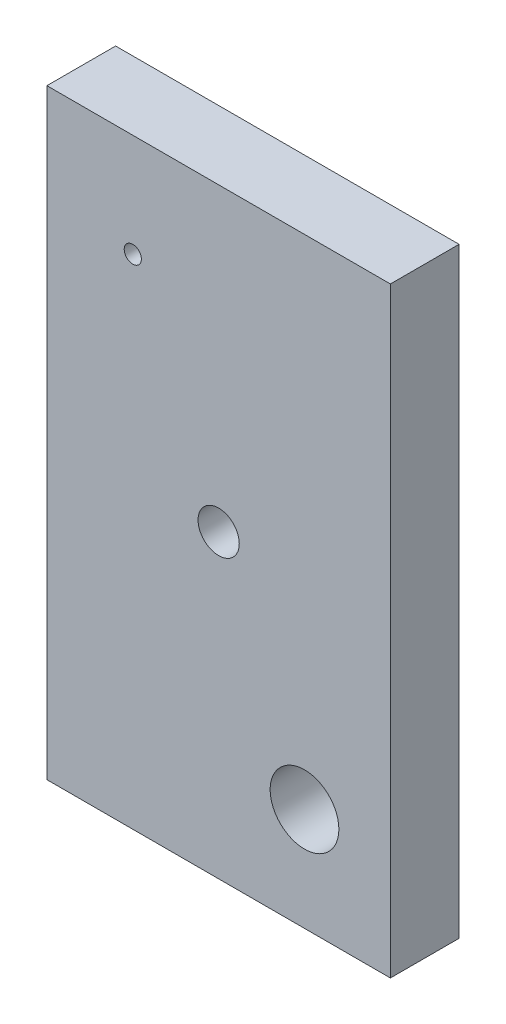
SolidWorks part; units mm, degrees
ref_plane "Front Plane" through (0, 0, 0) normal (0, 0, 1) x (1, 0, 0)
ref_plane "Top Plane" through (0, 0, 0) normal (0, 1, 0) x (1, 0, 0)
ref_plane "Right Plane" through (0, 0, 0) normal (1, 0, 0) x (0, 0, -1)
sketch "Sketch1" plane through (0, 0, 0) normal (0, 0, 1) x (1, 0, 0)
  line L1 (0, 0) -> (100, 0)
  line L2 (0, 0) -> (0, 175)
  line L3 (0, 175) -> (100, 175)
  line L4 (100, 0) -> (100, 175)
  dimension "D1" = 100
  dimension "D2" = 175
extrude "Boss-Extrude1" add sketch "Sketch1" against normal blind 20
hole_wizard "Ø5.0 (5) Diameter Hole1" positions "Sketch2" profile "Sketch3" hole size "Ø5.0" standard "ANSI Metric" end condition through all
sketch "Sketch2" plane through (0, 0, 0) normal (0, 0, 1) x (1, 0, 0)
  line L0 (0, 175) -> (0, 0) construction
  line L1 (100, 175) -> (0, 175) construction
  point P0 (25, 145)
  dimension "D1" = 25
  dimension "D2" = 30
sketch "Sketch3" plane through (25, 145, 0) normal (1, 0, 0) x (0, -1, 0)
  line L0 (0, 0) -> (0, 20)
  line L1 (0, 20) -> (2.5, 20)
  line L2 (2.5, 20) -> (2.5, 0)
  line L5 (2.5, 0) -> (0, 0)
  line L11 (0, -6.35) -> (0, 107.95) construction
  dimension "Thru Hole Dia." = 5
  dimension "Thru Hole Depth" = 20
hole_wizard "Ø12.0 (12) Diameter Hole1" positions "Sketch4" profile "Sketch5" hole size "Ø12.0" standard "ANSI Metric" end condition through all
sketch "Sketch4" plane through (0, 0, 0) normal (0, 0, 1) x (1, 0, 0)
  line L0 (100, 175) -> (0, 175) construction
  line L1 (0, 175) -> (0, 0) construction
  point P0 (50, 87.5)
  dimension "D1" = 87.5
  dimension "D2" = 50
sketch "Sketch5" plane through (50, 87.5, 0) normal (1, 0, 0) x (0, -1, 0)
  line L0 (0, 0) -> (0, 20)
  line L1 (0, 20) -> (6, 20)
  line L2 (6, 20) -> (6, 0)
  line L5 (6, 0) -> (0, 0)
  line L11 (0, -6.35) -> (0, 107.95) construction
  dimension "Thru Hole Dia." = 12
  dimension "Thru Hole Depth" = 20
hole_wizard "Ø20.0 (20) Diameter Hole1" positions "Sketch6" profile "Sketch7" hole size "Ø20.0" standard "ANSI Metric" end condition through all
sketch "Sketch6" plane through (0, 0, 0) normal (0, 0, 1) x (1, 0, 0)
  line L0 (100, 0) -> (100, 175) construction
  line L1 (0, 0) -> (100, 0) construction
  point P0 (75, 30)
  dimension "D1" = 25
  dimension "D2" = 30
sketch "Sketch7" plane through (75, 30, 0) normal (1, 0, 0) x (0, -1, 0)
  line L0 (0, 0) -> (0, 20)
  line L1 (0, 20) -> (10, 20)
  line L2 (10, 20) -> (10, 0)
  line L5 (10, 0) -> (0, 0)
  line L11 (0, -6.35) -> (0, 107.95) construction
  dimension "Thru Hole Dia." = 20
  dimension "Thru Hole Depth" = 20
